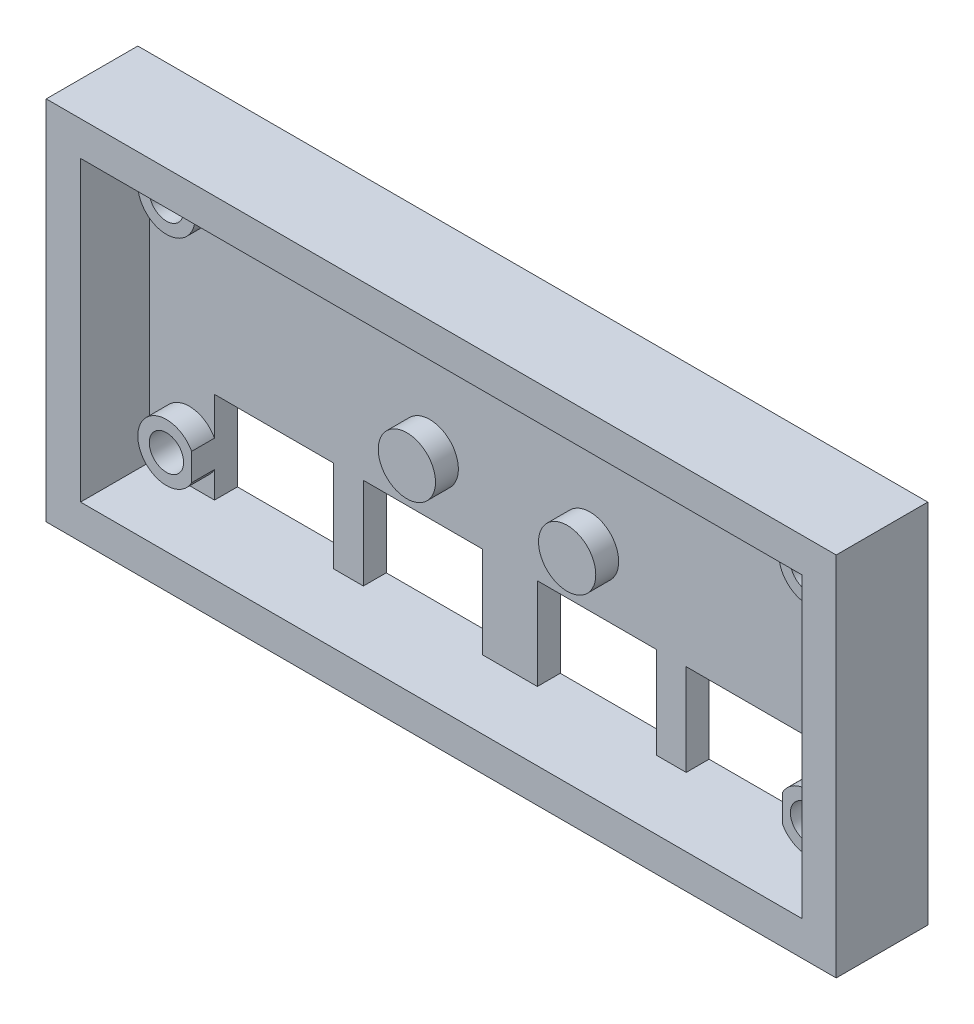
SolidWorks part; units mm, degrees
ref_plane "Front" through (0, 0, 0) normal (0, 0, 1) x (1, 0, 0)
ref_plane "Top" through (0, 0, 0) normal (0, 1, 0) x (1, 0, 0)
ref_plane "Right" through (0, 0, 0) normal (1, 0, 0) x (0, 0, -1)
sketch "Sketch1" plane through (0, 0, 0) normal (0, 0, 1) x (1, 0, 0)
  line L0 (-34.5, 16) -> (34.5, -16) construction
  line L1 (-34.5, 16) -> (34.5, 16)
  line L2 (-34.5, 16) -> (-34.5, -16)
  line L3 (-34.5, -16) -> (34.5, -16)
  line L4 (34.5, 16) -> (34.5, -16)
  dimension "D1" = 69
  dimension "D2" = 32
extrude "Boss-Extrude1" add sketch "Sketch1" along normal blind 2
sketch "Sketch2" plane through (0, 0, 2) normal (0, 0, 1) x (1, 0, 0)
  line L0 (-31.5, 0) -> (31.5, 0) construction
  line L1 (-31.5, 13) -> (31.5, 13)
  line L2 (-31.5, 13) -> (-31.5, -13)
  line L3 (-31.5, -13) -> (31.5, -13)
  line L4 (31.5, 13) -> (31.5, -13)
  line L5 (-34.5, 16) -> (-34.5, -16) construction
  line L6 (34.5, 16) -> (-34.5, 16) construction
  line L7 (0, 0) -> (0, -13) construction
  point P6 (45.3815, -13)
  line M23 (-34.5, 16) -> (-34.5, -16)
  line M24 (-34.5, -16) -> (34.5, -16)
  line M25 (34.5, -16) -> (34.5, 16)
  line M26 (34.5, 16) -> (-34.5, 16)
  dimension "D1" = 3
  dimension "D2" = 3
extrude "Boss-Extrude2" add sketch "Sketch2" along normal blind 6 contours L1 L4 L3 L2 M26 M23 M24 M25
sketch "Sketch3" plane through (0, 0, 2) normal (0, 0, 1) x (1, 0, 0)
  line L0 (0, -9.5) -> (0, 9.5) construction
  line L1 (-28, 9.5) -> (28, 9.5) construction
  line L2 (-28, 9.5) -> (-28, -9.5) construction
  line L3 (-28, -9.5) -> (28, -9.5) construction
  line L4 (28, 9.5) -> (28, -9.5) construction
  line L5 (-7, 0) -> (7, 0) construction
  circle A0 centre (-28, 9.5) radius 1.5
  circle A1 centre (28, 9.5) radius 1.5
  circle A2 centre (28, -9.5) radius 1.5
  circle A3 centre (-28, -9.5) radius 1.5
  circle A4 centre (-28, 9.5) radius 2.5
  circle A5 centre (-28, -9.5) radius 2.5
  circle A6 centre (28, -9.5) radius 2.5
  circle A7 centre (28, 9.5) radius 2.5
  circle A8 centre (-7, 0) radius 2.5
  circle A9 centre (7, 0) radius 2.5
  point P19 (0, 0)
  dimension "D3" = 3
  dimension "D4" = 5
  dimension "D1" = 19
  dimension "D2" = 56
  dimension "D5" = 14
extrude "Boss-Extrude3" add sketch "Sketch3" along normal blind 2
sketch "Sketch4" plane through (0, 0, 2) normal (0, 0, 1) x (1, 0, 0)
  line L0 (-31.5, -13) -> (31.5, -13) construction
  line L1 (-25.8, -5) -> (-15.4, -5)
  line L2 (-25.8, -5) -> (-25.8, -13)
  line L3 (-25.8, -13) -> (-15.4, -13)
  line L4 (-15.4, -5) -> (-15.4, -13)
  line L5 (0, 0) -> (0, -16) construction
  line L6 (-12.8, -13) -> (-2.4, -13)
  line L7 (-12.8, -13) -> (-12.8, -5)
  line L8 (-12.8, -5) -> (-2.4, -5)
  line L9 (-2.4, -13) -> (-2.4, -5)
  line L10 (2.4, -5) -> (12.8, -5)
  line L11 (2.4, -5) -> (2.4, -13)
  line L12 (2.4, -13) -> (12.8, -13)
  line L13 (12.8, -5) -> (12.8, -13)
  line L14 (15.4, -13) -> (25.8, -13)
  line L15 (15.4, -13) -> (15.4, -5)
  line L16 (15.4, -5) -> (25.8, -5)
  line L17 (25.8, -13) -> (25.8, -5)
  line L18 (-34.5, -16) -> (34.5, -16) construction
  circle A0 centre (28, 9.5) radius 1.5 construction
  circle A1 centre (28, -9.5) radius 1.5 construction
  circle A2 centre (-28, -9.5) radius 1.5 construction
  circle A3 centre (-28, 9.5) radius 1.5 construction
  circle A4 centre (28, 9.5) radius 1.5
  circle A5 centre (28, -9.5) radius 1.5
  circle A6 centre (-28, -9.5) radius 1.5
  circle A7 centre (-28, 9.5) radius 1.5
  dimension "D1" = 2.6
  dimension "D2" = 4.8
  dimension "D3" = 2.6
  dimension "D4" = 10.4
  dimension "D5" = 8
extrude "Cut-Extrude1" cut sketch "Sketch4" against normal through all both and the other way through all
fillet "Fillet1" [suppressed] radius 3
equation "\"D3@Sketch4\"=\"D1@Sketch4\""
